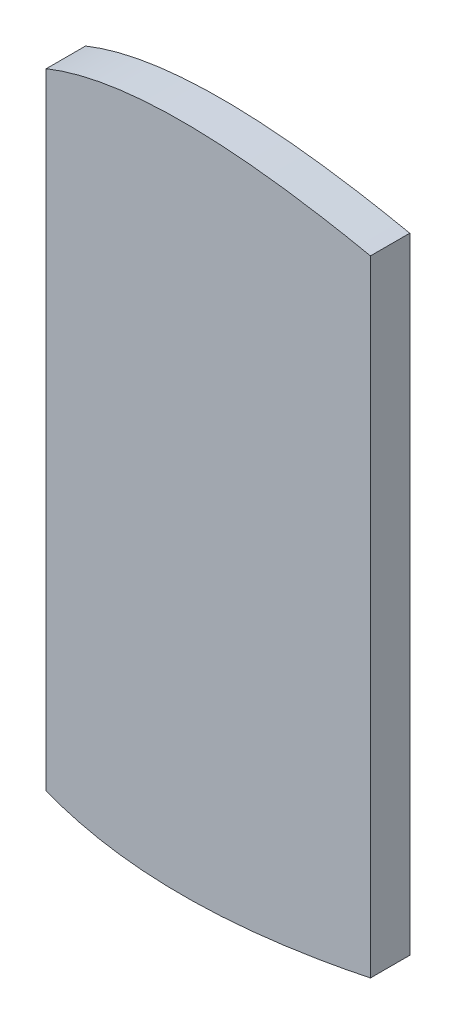
SolidWorks part; units mm, degrees
material "Plain Carbon Steel"
ref_plane "Front Plane" through (0, 0, 0) normal (0, 0, 1) x (1, 0, 0)
ref_plane "Top Plane" through (0, 0, 0) normal (0, 1, 0) x (1, 0, 0)
ref_plane "Right Plane" through (0, 0, 0) normal (1, 0, 0) x (0, 0, -1)
sketch "Sketch1" plane through (0, 0, 0) normal (0, 0, 1) x (1, 0, 0)
  line L0 (0, 0) -> (102.8599, 0) construction
  line L1 (74.1855, 60.602) -> (74.1855, -70.576) construction
  line L2 (37.8955, 48) -> (110.4755, 48)
  line L3 (110.4755, 48) -> (110.4755, -92)
  line L4 (110.4755, -92) -> (37.8955, -92)
  line L5 (37.8955, -92) -> (37.8955, 48)
  line L6 (37.8955, 48) -> (62.6455, 58) construction
  line L7 (62.6455, 58) -> (110.4755, 48) construction
  line L8 (37.8955, -92) -> (62.6455, -102) construction
  line L9 (62.6455, -102) -> (110.4755, -92) construction
  spline S0 degree 2 poles (37.8955, 48) (62.6455, 58) (110.4755, 48) knots 0 0 0 1 1 1
  spline S1 degree 2 poles (37.8955, -92) (62.6455, -102) (110.4755, -92) knots 0 0 0 1 1 1
  dimension "D1" = 72.58
  dimension "D2" = 72.58
  dimension "D3" = 36.29
  dimension "D4" = 36.29
  dimension "D5" = 48
  dimension "D6" = 140
  dimension "D7" = 10
  dimension "D8" = 10
extrude "Boss-Extrude1" add sketch "Sketch1" along normal blind 8.8 contours S0 L2 | L5 L4 L3 L2 | L4 S1
